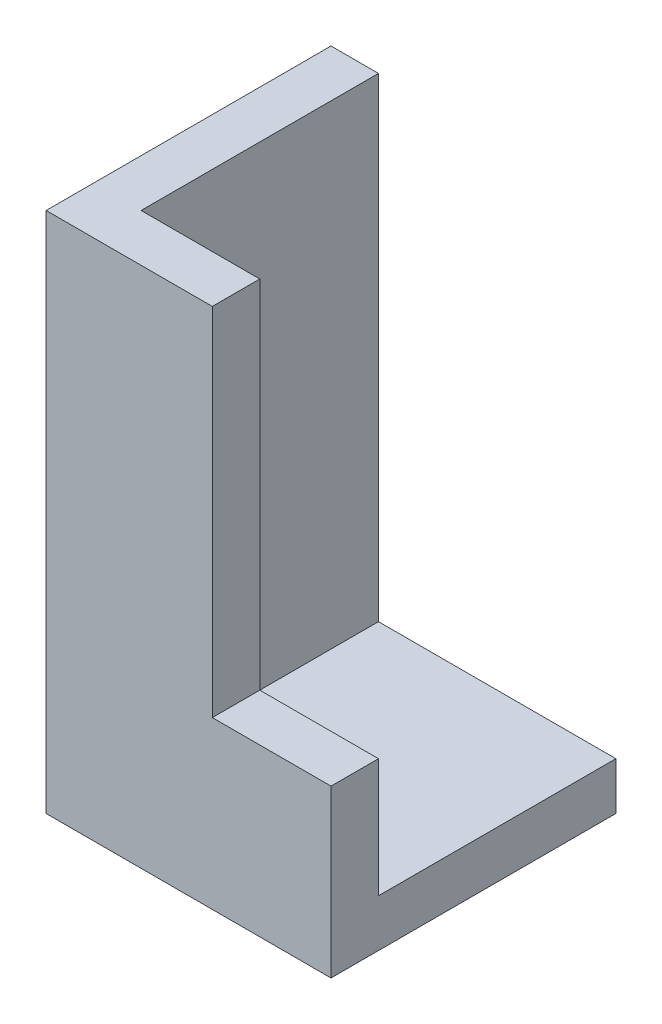
SolidWorks part; units mm, degrees
ref_plane "Front Plane" through (0, 0, 0) normal (0, 0, 1) x (1, 0, 0)
ref_plane "Top Plane" through (0, 0, 0) normal (0, 1, 0) x (1, 0, 0)
ref_plane "Right Plane" through (0, 0, 0) normal (1, 0, 0) x (0, 0, -1)
sketch "Sketch1" plane through (0, 0, 0) normal (0, 0, 1) x (1, 0, 0)
  line L0 (0, 110) -> (10, 110)
  line L1 (0, 0) -> (60, 0)
  line L2 (0, 0) -> (0, 110)
  line L3 (60, 10) -> (60, 0)
  line L5 (10, 110) -> (10, 10)
  line L6 (10, 10) -> (60, 10)
  dimension "D1" = 110
extrude "Boss-Extrude1" add sketch "Sketch1" along normal blind 50
sketch "Sketch2" plane through (0, 0, 50) normal (0, 0, 1) x (1, 0, 0)
  line L0 (0, 110) -> (35, 110)
  line L1 (0, 110) -> (0, 0) construction
  line L2 (10, 110) -> (0, 110) construction
  line L3 (35, 110) -> (35, 35)
  line L4 (35, 35) -> (60, 35)
  line L5 (60, 35) -> (60, 0)
  line L6 (60, 0) -> (60, 10) construction
  line L7 (60, 0) -> (0, 0)
  line L8 (0, 0) -> (0, 110)
  dimension "D1" = 35
  dimension "D2" = 35
extrude "Boss-Extrude2" add sketch "Sketch2" along normal blind 10
